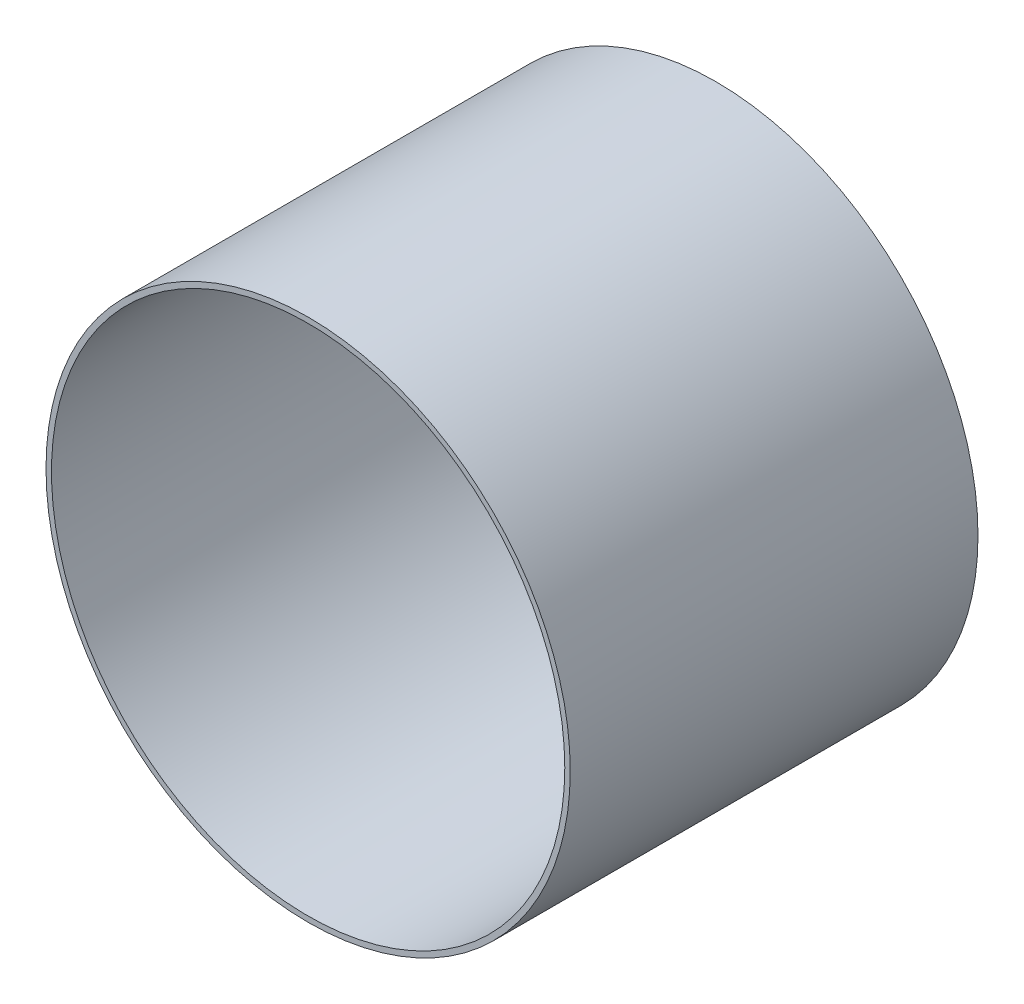
SolidWorks part; units mm, degrees
ref_plane "Front Plane" through (0, 0, 0) normal (0, 0, 1) x (1, 0, 0)
ref_plane "Top Plane" through (0, 0, 0) normal (0, 1, 0) x (1, 0, 0)
ref_plane "Right Plane" through (0, 0, 0) normal (1, 0, 0) x (0, 0, -1)
sketch "Sketch4" plane through (0, 0, 0) normal (0, 0, 1) x (-1, 0, 0)
  circle A0 centre (-18.9828, -130.0427) radius 3 construction
  circle A1 centre (-50.7836, -160.2207) radius 3 construction
  circle A2 centre (-80.9615, -128.4199) radius 3 construction
  circle A4 centre (-49.9722, -129.2313) radius 35.25
  circle A6 centre (-50.7836, -160.2207) radius 1.7 construction
  circle A7 centre (-18.9828, -130.0427) radius 1.7 construction
  circle A8 centre (-49.1608, -98.2419) radius 1.7 construction
  circle A9 centre (-80.9615, -128.4199) radius 1.7 construction
  circle A11 centre (-49.9722, -129.2313) radius 36
  dimension "D2" = 70.5
  dimension "D3" = 6
  dimension "D4" = 6
  dimension "D5" = 6
  dimension "D6" = 72
extrude "Boss-Extrude2" add sketch "Sketch4" along normal blind 56
sketch "Sketch7" plane through (0, 0, 0) normal (0, 0, 1) x (-1, 0, 0)
  line L8 (-27.2483, -155.3593) -> (-27.2876, -156.8623)
  line L10 (-33.0463, -155.2075) -> (-33.1927, -160.7989)
  circle A0 centre (-30.1473, -155.2834) radius 2.9
  arc A10 (-33.2941, -160.8526) -> (-27.2876, -156.8623) centre (-49.9722, -129.2313) ccw
  dimension "D5" = 5.8
